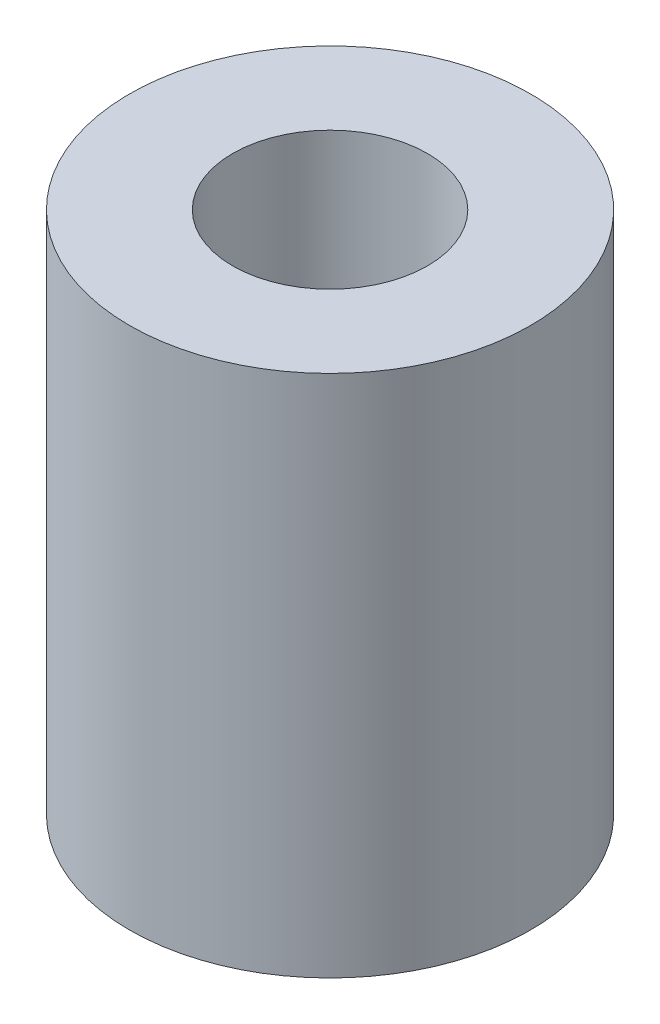
SolidWorks part; units mm, degrees
ref_plane "Front Plane" through (0, 0, 0) normal (0, 0, 1) x (1, 0, 0)
ref_plane "Top Plane" through (0, 0, 0) normal (0, 1, 0) x (1, 0, 0)
ref_plane "Right Plane" through (0, 0, 0) normal (1, 0, 0) x (0, 0, -1)
sketch "Sketch1" plane through (0, 0, 0) normal (0, 1, 0) x (1, 0, 0)
  circle A0 centre (0, 0) radius 3.5
  circle A1 centre (0, 0) radius 1.7
extrude "Boss-Extrude1" add sketch "Sketch1" along normal blind 9.137
